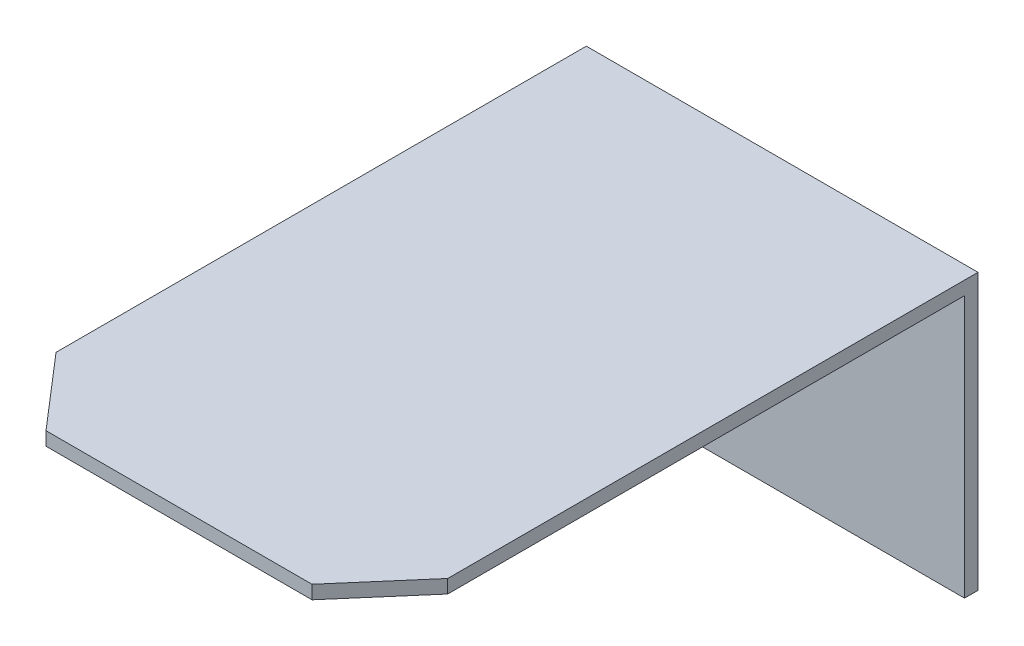
SolidWorks part; units mm, degrees
ref_plane "Front Plane" through (0, 0, 0) normal (0, 0, 1) x (1, 0, 0)
ref_plane "Top Plane" through (0, 0, 0) normal (0, 1, 0) x (1, 0, 0)
ref_plane "Right Plane" through (0, 0, 0) normal (1, 0, 0) x (0, 0, -1)
sketch "Sketch1" plane through (0, 0, 0) normal (0, 1, 0) x (1, 0, 0)
  line L1 (0, 0) -> (34.671, 0)
  line L2 (0, 0) -> (0, 52.197)
  line L3 (0, 52.197) -> (34.671, 52.197)
  line L4 (34.671, 0) -> (34.671, 52.197)
  dimension "D1" = 52.197
  dimension "D2" = 34.671
extrude "Boss-Extrude1" add sketch "Sketch1" along normal blind 1.1938
ref_plane "Plane1" through (34.671, 1.1938, -52.197) normal (-1, 0, 0) x (0, 0, 1)
sketch "Sketch3" plane through (0, 0, -52.197) normal (0, 0, -1) x (-1, 0, 0)
  line L0 (-34.671, 1.1938) -> (0, 1.1938) construction
  line L1 (-34.671, 1.1938) -> (0, 1.1938)
  line L2 (-34.671, 1.1938) -> (-34.671, -23.1902)
  line L3 (-34.671, -23.1902) -> (0, -23.1902)
  line L4 (0, 1.1938) -> (0, -23.1902)
  line L5 (-34.671, 1.1938) -> (-34.671, 0) construction
  line L6 (0, 1.1938) -> (0, 0) construction
  dimension "D1" = 0
  dimension "D2" = 0
  dimension "D3" = 24.384
extrude "Boss-Extrude2" add sketch "Sketch3" along normal blind 1.1938
sketch "Sketch4" plane through (0, 0, 0) normal (0, -1, 0) x (-1, 0, 0)
  line L0 (-34.671, 6.4516) -> (-29.1084, 0)
  line L1 (-34.671, 0) -> (-34.671, 52.197) construction
  line L2 (0, 0) -> (-34.671, 0) construction
  line L4 (-17.3355, 0) -> (-17.3355, 52.197) construction
  line L5 (-34.671, 52.197) -> (0, 52.197) construction
  line L6 (0, 6.4516) -> (-5.5626, 0)
  line M1 (0, 0) -> (0, 52.197)
  line M3 (-34.671, 52.197) -> (-34.671, 0)
  line M4 (-34.671, 0) -> (0, 0)
  dimension "D1" = 5.5626
  dimension "D2" = 6.4516
extrude "Cut-Extrude1" cut sketch "Sketch4" along normal through all and the other way through all contours L6 M1 M4 | L0 M3 M4
